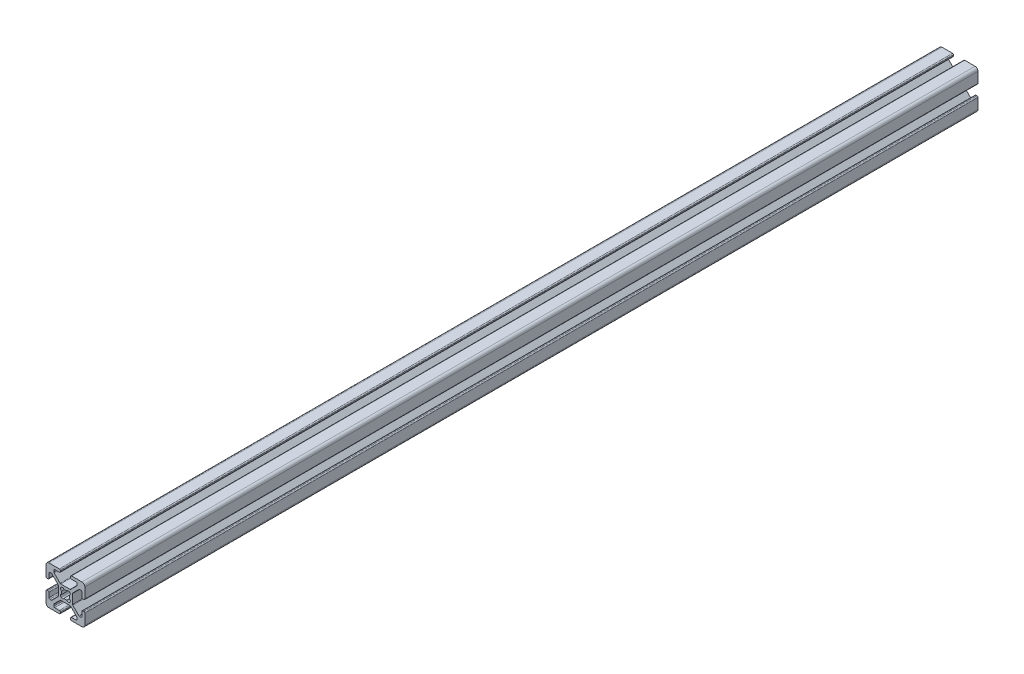
SolidWorks part; units mm, degrees
ref_plane "Front Plane" through (0, 0, 0) normal (0, 0, 1) x (1, 0, 0)
ref_plane "Top Plane" through (0, 0, 0) normal (0, 1, 0) x (1, 0, 0)
ref_plane "Right Plane" through (0, 0, 0) normal (1, 0, 0) x (0, 0, -1)
sketch "Sketch1" plane through (0, 0, 0) normal (0, 0, 1) x (1, 0, 0)
  line L0 (-5.0323, -0.3411) -> (-5.5163, -0.3411)
  line L1 (-6.0243, 0.1669) -> (-6.0243, 2.5159)
  line L2 (-4.5243, 0.1669) -> (-4.5243, 5.5289)
  line L3 (-10.8693, -5.355) -> (-10.8693, -0.5871)
  line L4 (-7.2582, 3.0239) -> (-6.5323, 3.0239)
  line L5 (-7.6174, 2.8752) -> (-10.7205, -0.2279)
  line L6 (-5.0323, -5.6011) -> (-5.5163, -5.6011)
  line L7 (-4.5243, -6.1091) -> (-4.5243, -11.4711)
  line L8 (-6.0243, -6.1091) -> (-6.0243, -8.4581)
  line L9 (-7.2582, -8.9661) -> (-6.5323, -8.9661)
  line L10 (-7.6174, -8.8173) -> (-10.7205, -5.7142)
  line L11 (-12.3994, -5.2756) -> (-12.2198, -5.096)
  line L12 (-17.1543, 6.5209) -> (-17.1543, 6.0369)
  line L13 (-17.6623, 7.0289) -> (-23.0243, 7.0289)
  line L14 (-17.6623, 5.5289) -> (-20.0113, 5.5289)
  line L15 (-12.1404, 0.6839) -> (-16.9082, 0.6839)
  line L16 (-20.5193, 4.295) -> (-20.5193, 5.0209)
  line L17 (-20.3705, 3.9358) -> (-17.2674, 0.8327)
  line L18 (-11.8943, 6.5209) -> (-11.8943, 6.0369)
  line L19 (-11.3863, 7.0289) -> (-6.0243, 7.0289)
  line L20 (-11.3863, 5.5289) -> (-9.0373, 5.5289)
  line L21 (-8.5293, 4.295) -> (-8.5293, 5.0209)
  line L22 (-8.6781, 3.9358) -> (-11.7812, 0.8327)
  line L23 (-12.2198, -0.8462) -> (-12.3994, -0.6666)
  line L24 (-24.0163, -5.6011) -> (-23.5323, -5.6011)
  line L25 (-24.5243, -6.1091) -> (-24.5243, -11.4711)
  line L26 (-23.0243, -6.1091) -> (-23.0243, -8.4581)
  line L27 (-18.1793, -0.5871) -> (-18.1793, -5.355)
  line L28 (-21.7904, -8.9661) -> (-22.5163, -8.9661)
  line L29 (-21.4312, -8.8173) -> (-18.3281, -5.7142)
  line L30 (-24.0163, -0.3411) -> (-23.5323, -0.3411)
  line L31 (-24.5243, 0.1669) -> (-24.5243, 5.5289)
  line L32 (-23.0243, 0.1669) -> (-23.0243, 2.5159)
  line L33 (-21.7904, 3.0239) -> (-22.5163, 3.0239)
  line L34 (-21.4312, 2.8752) -> (-18.3281, -0.2279)
  line L35 (-16.6492, -0.6666) -> (-16.8288, -0.8462)
  line L36 (-11.8943, -12.4631) -> (-11.8943, -11.9791)
  line L37 (-11.3863, -12.9711) -> (-6.0243, -12.9711)
  line L38 (-11.3863, -11.4711) -> (-9.0373, -11.4711)
  line L39 (-16.9082, -6.6261) -> (-12.1404, -6.6261)
  line L40 (-8.5293, -10.2371) -> (-8.5293, -10.9631)
  line L41 (-8.6781, -9.8779) -> (-11.7812, -6.7748)
  line L42 (-17.1543, -12.4631) -> (-17.1543, -11.9791)
  line L43 (-17.6623, -12.9711) -> (-23.0243, -12.9711)
  line L44 (-17.6623, -11.4711) -> (-20.0113, -11.4711)
  line L45 (-20.5193, -10.2371) -> (-20.5193, -10.9631)
  line L46 (-20.3705, -9.8779) -> (-17.2674, -6.7748)
  line L47 (-16.8288, -5.096) -> (-16.6492, -5.2756)
  arc A0 (-15.3283, -4.9062) -> (-13.7203, -4.9062) centre (-14.5243, -2.9711) ccw
  arc A1 (-6.0243, 2.5159) -> (-6.5323, 3.0239) centre (-6.5323, 2.5159) ccw
  arc A2 (-7.2582, 3.0239) -> (-7.6174, 2.8752) centre (-7.2582, 2.5159) ccw
  arc A3 (-10.7205, -0.2279) -> (-10.8693, -0.5871) centre (-10.3613, -0.5871) ccw
  arc A4 (-10.8693, -5.355) -> (-10.7205, -5.7142) centre (-10.3613, -5.355) ccw
  arc A5 (-7.6174, -8.8173) -> (-7.2582, -8.9661) centre (-7.2582, -8.4581) ccw
  arc A6 (-6.5323, -8.9661) -> (-6.0243, -8.4581) centre (-6.5323, -8.4581) ccw
  arc A7 (-5.5163, -5.6011) -> (-6.0243, -6.1091) centre (-5.5163, -6.1091) ccw
  arc A8 (-4.5243, -6.1091) -> (-5.0323, -5.6011) centre (-5.0323, -6.1091) ccw
  arc A9 (-5.0323, -0.3411) -> (-4.5243, 0.1669) centre (-5.0323, 0.1669) ccw
  arc A10 (-6.0243, 0.1669) -> (-5.5163, -0.3411) centre (-5.5163, 0.1669) ccw
  arc A11 (-13.7203, -4.9062) -> (-12.3994, -5.2756) centre (-12.9559, -4.7191) ccw
  arc A12 (-12.2198, -5.096) -> (-12.5892, -3.775) centre (-12.7763, -4.5395) ccw
  arc A13 (-17.1543, 6.5209) -> (-17.6623, 7.0289) centre (-17.6623, 6.5209) ccw
  arc A14 (-17.6623, 5.5289) -> (-17.1543, 6.0369) centre (-17.6623, 6.0369) ccw
  arc A15 (-12.5892, -3.775) -> (-12.5892, -2.1671) centre (-14.5243, -2.9711) ccw
  arc A16 (-17.2674, 0.8327) -> (-16.9082, 0.6839) centre (-16.9082, 1.1919) ccw
  arc A17 (-20.0113, 5.5289) -> (-20.5193, 5.0209) centre (-20.0113, 5.0209) ccw
  arc A18 (-20.5193, 4.295) -> (-20.3705, 3.9358) centre (-20.0113, 4.295) ccw
  arc A19 (-11.8943, 6.0369) -> (-11.3863, 5.5289) centre (-11.3863, 6.0369) ccw
  arc A20 (-11.3863, 7.0289) -> (-11.8943, 6.5209) centre (-11.3863, 6.5209) ccw
  arc A21 (-8.5293, 5.0209) -> (-9.0373, 5.5289) centre (-9.0373, 5.0209) ccw
  arc A22 (-8.6781, 3.9358) -> (-8.5293, 4.295) centre (-9.0373, 4.295) ccw
  arc A23 (-12.1404, 0.6839) -> (-11.7812, 0.8327) centre (-12.1404, 1.1919) ccw
  arc A24 (-12.5892, -2.1671) -> (-12.2198, -0.8462) centre (-12.7763, -1.4027) ccw
  arc A25 (-12.3994, -0.6666) -> (-13.7203, -1.0359) centre (-12.9559, -1.223) ccw
  arc A26 (-24.0163, -5.6011) -> (-24.5243, -6.1091) centre (-24.0163, -6.1091) ccw
  arc A27 (-23.0243, -6.1091) -> (-23.5323, -5.6011) centre (-23.5323, -6.1091) ccw
  arc A28 (-13.7203, -1.0359) -> (-15.3283, -1.0359) centre (-14.5243, -2.9711) ccw
  arc A29 (-18.3281, -5.7142) -> (-18.1793, -5.355) centre (-18.6873, -5.355) ccw
  arc A30 (-23.0243, -8.4581) -> (-22.5163, -8.9661) centre (-22.5163, -8.4581) ccw
  arc A31 (-21.7904, -8.9661) -> (-21.4312, -8.8173) centre (-21.7904, -8.4581) ccw
  arc A32 (-23.5323, -0.3411) -> (-23.0243, 0.1669) centre (-23.5323, 0.1669) ccw
  arc A33 (-24.5243, 0.1669) -> (-24.0163, -0.3411) centre (-24.0163, 0.1669) ccw
  arc A34 (-22.5163, 3.0239) -> (-23.0243, 2.5159) centre (-22.5163, 2.5159) ccw
  arc A35 (-21.4312, 2.8752) -> (-21.7904, 3.0239) centre (-21.7904, 2.5159) ccw
  arc A36 (-18.1793, -0.5871) -> (-18.3281, -0.2279) centre (-18.6873, -0.5871) ccw
  arc A37 (-15.3283, -1.0359) -> (-16.6492, -0.6666) centre (-16.0927, -1.223) ccw
  arc A38 (-16.8288, -0.8462) -> (-16.4594, -2.1671) centre (-16.2723, -1.4027) ccw
  arc A39 (-11.8943, -12.4631) -> (-11.3863, -12.9711) centre (-11.3863, -12.4631) ccw
  arc A40 (-11.3863, -11.4711) -> (-11.8943, -11.9791) centre (-11.3863, -11.9791) ccw
  arc A41 (-16.4594, -2.1671) -> (-16.4594, -3.775) centre (-14.5243, -2.9711) ccw
  arc A42 (-11.7812, -6.7748) -> (-12.1404, -6.6261) centre (-12.1404, -7.1341) ccw
  arc A43 (-9.0373, -11.4711) -> (-8.5293, -10.9631) centre (-9.0373, -10.9631) ccw
  arc A44 (-8.5293, -10.2371) -> (-8.6781, -9.8779) centre (-9.0373, -10.2371) ccw
  arc A45 (-17.1543, -11.9791) -> (-17.6623, -11.4711) centre (-17.6623, -11.9791) ccw
  arc A46 (-17.6623, -12.9711) -> (-17.1543, -12.4631) centre (-17.6623, -12.4631) ccw
  arc A47 (-20.5193, -10.9631) -> (-20.0113, -11.4711) centre (-20.0113, -10.9631) ccw
  arc A48 (-20.3705, -9.8779) -> (-20.5193, -10.2371) centre (-20.0113, -10.2371) ccw
  arc A49 (-16.9082, -6.6261) -> (-17.2674, -6.7748) centre (-16.9082, -7.1341) ccw
  arc A50 (-16.4594, -3.775) -> (-16.8288, -5.096) centre (-16.2723, -4.5395) ccw
  arc A51 (-16.6492, -5.2756) -> (-15.3283, -4.9062) centre (-16.0927, -4.7191) ccw
  arc A52 (-4.5243, 5.5289) -> (-6.0243, 7.0289) centre (-6.0243, 5.5289) ccw
  arc A53 (-6.0243, -12.9711) -> (-4.5243, -11.4711) centre (-6.0243, -11.4711) ccw
  arc A54 (-24.5243, -11.4711) -> (-23.0243, -12.9711) centre (-23.0243, -11.4711) ccw
  arc A55 (-23.0243, 7.0289) -> (-24.5243, 5.5289) centre (-23.0243, 5.5289) ccw
extrude "Extrude1" add sketch "Sketch1" along normal blind 460
